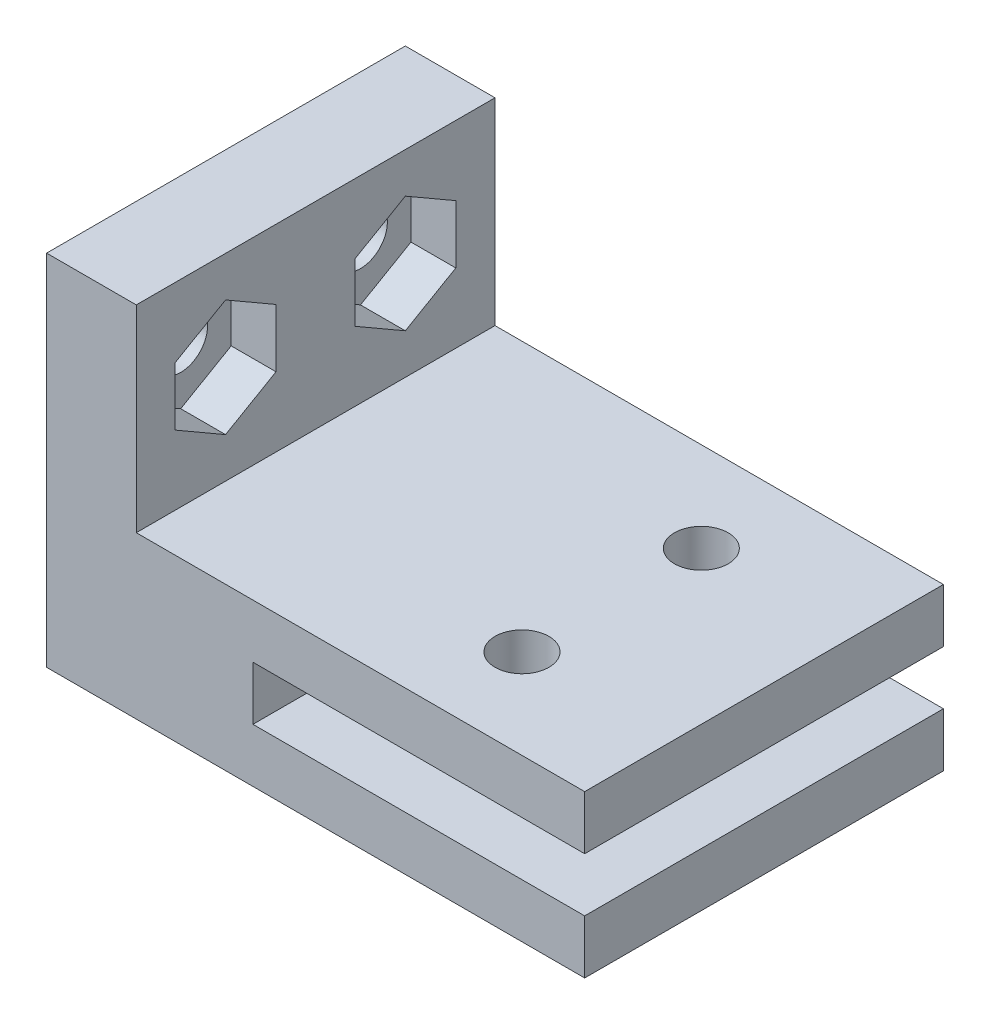
SolidWorks part; units mm, degrees
ref_plane "Front Plane" through (0, 0, 0) normal (0, 0, 1) x (1, 0, 0)
ref_plane "Top Plane" through (0, 0, 0) normal (0, 1, 0) x (1, 0, 0)
ref_plane "Right Plane" through (0, 0, 0) normal (1, 0, 0) x (0, 0, -1)
sketch "Sketch2" plane through (0, 0, 0) normal (0, 0, 1) x (1, 0, 0)
  line L1 (20, -10) -> (-20, -10)
  line L2 (20, -10) -> (20, 10)
  line L3 (20, 10) -> (-20, 10)
  line L4 (-20, -10) -> (-20, 10)
  line L5 (20, -10) -> (-20, 10) construction
  line L6 (20, 10) -> (-20, -10) construction
  point P0 (0, 0)
  dimension "D1" = 40
  dimension "D2" = 20
extrude "Boss-Extrude2" add sketch "Sketch2" along normal blind 20
sketch "Sketch3" plane through (-20, 0, 0) normal (-1, 0, 0) x (0, 0, 1)
  line L4 (0, 10) -> (0, -10)
  line L5 (0, -10) -> (20, -10)
  line L6 (20, -10) -> (20, 10)
  line L7 (20, 10) -> (0, 10)
  line L8 (0, 10) -> (0, -10)
  line L9 (0, -10) -> (20, -10)
  line L10 (20, -10) -> (20, 10)
  line L11 (20, 10) -> (0, 10)
  dimension "D1" = 0
extrude "Cut-Extrude1" cut sketch "Sketch3" against normal blind 10
sketch "Sketch4" plane through (0, 0, 20) normal (0, 0, 1) x (1, 0, 0)
  line L0 (20, -7) -> (1.5037, -7)
  line L1 (1.5037, -7) -> (1.5037, -4)
  line L2 (1.5037, -4) -> (20, -4)
  line L3 (20, -4) -> (20, 0)
  line L4 (20, 10) -> (-10, 10)
  line L5 (-10, 10) -> (-10, -10)
  line L6 (-10, -10) -> (20, -10)
  line L7 (20, -10) -> (20, 10)
  line L8 (20, 10) -> (-10, 10)
  line L9 (-10, 10) -> (-10, -10)
  line L10 (-10, -10) -> (20, -10)
  line L11 (20, -10) -> (20, 10)
  line L12 (20, -1) -> (-5, -1)
  line L13 (-5, -1) -> (-5, 10)
  line L14 (-5, 10) -> (-10, 10)
  line L15 (-10, -10) -> (20, -10)
  point P11 (11.5037, -7)
  line M7 (20, 10) -> (-10, 10)
  line M10 (20, -10) -> (20, 10)
  dimension "D2" = 3
  dimension "D3" = 3
  dimension "D4" = 3
  dimension "D5" = 5
  dimension "D6" = 10
  dimension "D1" = 0
extrude "Cut-Extrude2" cut sketch "Sketch4" against normal through all contours L13 L12 L11 M7 | L2 L1 L0 M10
sketch "Sketch5" plane through (-5, 0, 0) normal (1, 0, 0) x (0, 0, -1)
  line L3 (0, 10) -> (-20, 10) construction
  line L4 (-20, -1) -> (-20, 10) construction
  line L5 (0, -1) -> (-20, -1) construction
  line L6 (0, -1) -> (0, 10) construction
  line L7 (0, 10) -> (-20, 10)
  line L8 (-20, -1) -> (-20, 10)
  line L9 (0, -1) -> (-20, -1)
  line L10 (0, -1) -> (0, 10)
  line L14 (-14.9953, 7.7908) -> (-17.8594, 6.1699)
  line L15 (-17.8594, 6.1699) -> (-17.8877, 2.8791)
  line L16 (-17.8877, 2.8791) -> (-15.0519, 1.2092)
  line L17 (-15.0519, 1.2092) -> (-12.1879, 2.8301)
  line L18 (-12.1879, 2.8301) -> (-12.1596, 6.1209)
  line L19 (-12.1596, 6.1209) -> (-14.9953, 7.7908)
  line L20 (-5, 7.7909) -> (-7.85, 6.1454)
  line L21 (-7.85, 6.1454) -> (-7.85, 2.8546)
  line L22 (-7.85, 2.8546) -> (-5, 1.2091)
  line L23 (-5, 1.2091) -> (-2.15, 2.8546)
  line L24 (-2.15, 2.8546) -> (-2.15, 6.1454)
  line L25 (-2.15, 6.1454) -> (-5, 7.7909)
  line L26 (-14.9953, 7.7908) -> (-17.8594, 6.1699)
  line L27 (-17.8594, 6.1699) -> (-17.8877, 2.8791)
  line L28 (-17.8877, 2.8791) -> (-15.0519, 1.2092)
  line L29 (-15.0519, 1.2092) -> (-12.1879, 2.8301)
  line L30 (-12.1879, 2.8301) -> (-12.1596, 6.1209)
  line L31 (-12.1596, 6.1209) -> (-14.9953, 7.7908)
  line L35 (-17.8738, 4.5) -> (-17.8736, 4.5) construction
  line L37 (-12.1736, 4.5) -> (-12.1735, 4.5) construction
  circle A0 centre (-15.0236, 4.5) radius 2.85 construction
  circle A1 centre (-5, 4.5) radius 2.85 construction
  circle A2 centre (-15.0236, 4.5) radius 1.5
  circle A3 centre (-5, 4.5) radius 1.5
  circle A4 centre (-15.0236, 4.5) radius 2.85 construction
  dimension "D3" = 3
  dimension "D4" = 3
  dimension "D5" = 5.7
  dimension "D6" = 5.7
extrude "Cut-Extrude3" cut sketch "Sketch5" against normal through all contours A2 | A3
sketch "Sketch8" plane through (-5, 0, 0) normal (1, 0, 0) x (0, 0, -1)
  line L1 (-15.0236, 7.7505) -> (-17.8386, 6.1252)
  line L2 (-17.8386, 6.1252) -> (-17.8386, 2.8748)
  line L3 (-17.8386, 2.8748) -> (-15.0236, 1.2495)
  line L4 (-20, 10) -> (-20, -1)
  line L5 (-20, -1) -> (0, -1)
  line L6 (0, -1) -> (0, 10)
  line L7 (0, 10) -> (-20, 10)
  line L8 (-20, 10) -> (-20, -1)
  line L9 (-20, -1) -> (0, -1)
  line L10 (0, -1) -> (0, 10)
  line L11 (0, 10) -> (-20, 10)
  line L12 (-15.0236, 1.2495) -> (-12.2086, 2.8748)
  line L13 (-12.2086, 2.8748) -> (-12.2086, 6.1252)
  line L14 (-12.2086, 6.1252) -> (-15.0236, 7.7505)
  line L15 (-5, 7.7505) -> (-7.815, 6.1252)
  line L16 (-7.815, 6.1252) -> (-7.815, 2.8748)
  line L17 (-7.815, 2.8748) -> (-5, 1.2495)
  line L18 (-5, 1.2495) -> (-2.185, 2.8748)
  line L19 (-2.185, 2.8748) -> (-2.185, 6.1252)
  line L20 (-2.185, 6.1252) -> (-5, 7.7505)
  circle A0 centre (-5, 4.5) radius 1.5 construction
  circle A1 centre (-15.0236, 4.5) radius 1.5 construction
  circle A2 centre (-5, 4.5) radius 1.5
  circle A3 centre (-15.0236, 4.5) radius 1.5
  circle A4 centre (-15.0236, 4.5) radius 2.815 construction
  circle A5 centre (-5, 4.5) radius 2.815 construction
  circle M9 centre (-5, 4.5) radius 1.5
  circle M10 centre (-15.0236, 4.5) radius 1.5
  dimension "D2" = 5.63
  dimension "D3" = 5.63
  dimension "D1" = 0
extrude "Cut-Extrude4" cut sketch "Sketch8" against normal blind 2.5 contours L13 L14 L1 L2 L3 L12 M10 | L19 L20 L15 L16 L17 L18 M9
sketch "Sketch9" plane through (0, -1, 0) normal (0, 1, 0) x (1, 0, 0)
  line L1 (11.5037, -1004.5242) -> (11.5037, 48995.4758) construction
  line L2 (1.5037, 0) -> (1.5037, -20) construction
  line L4 (-5, -20) -> (20, -20)
  line L5 (20, -20) -> (20, 0)
  line L6 (20, 0) -> (-5, 0)
  line L7 (-5, 0) -> (-5, -20)
  line L11 (-5, 0) -> (-5, -20)
  circle A0 centre (11.5037, -15) radius 1.5
  circle A1 centre (11.5037, -5) radius 1.5
  dimension "D2" = 10
  dimension "D3" = 10
  dimension "D1" = 0
extrude "Cut-Extrude6" cut sketch "Sketch9" against normal through all contours L1 A1 | A1 L1 | L1 A0 | A0 L1
